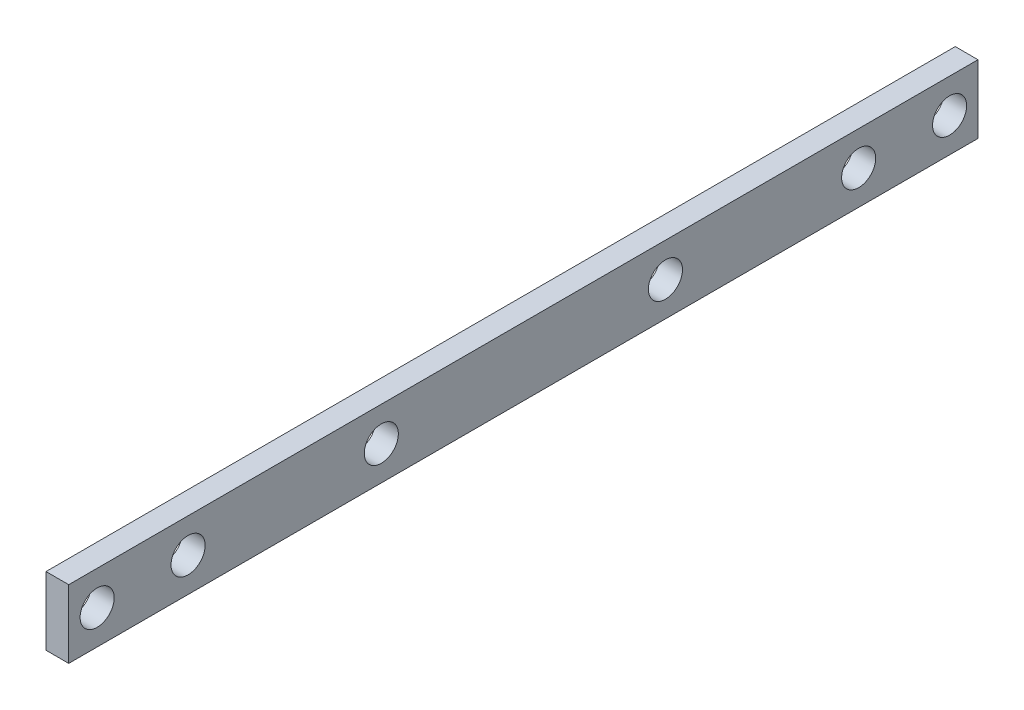
SolidWorks part; units mm, degrees
ref_plane "前视基准面" through (0, 0, 0) normal (0, 0, 1) x (1, 0, 0)
ref_plane "上视基准面" through (0, 0, 0) normal (0, 1, 0) x (1, 0, 0)
ref_plane "右视基准面" through (0, 0, 0) normal (1, 0, 0) x (0, 0, -1)
sketch "草图1" plane through (0, 0, 0) normal (1, 0, 0) x (0, 0, -1)
  line L0 (-40, 0) -> (40, 0) construction
  line L1 (-40, -3) -> (40, -3)
  line L2 (-40, -3) -> (-40, 3)
  line L3 (-40, 3) -> (40, 3)
  line L4 (40, -3) -> (40, 3)
  line L5 (-40, -3) -> (40, 3) construction
  line L6 (-40, 3) -> (40, -3) construction
  circle A0 centre (-37.5, 0) radius 1.5
  circle A1 centre (-12.5, 0) radius 1.5
  circle A2 centre (12.5, 0) radius 1.5
  circle A3 centre (37.5, 0) radius 1.5
  circle A4 centre (-29.5, 0) radius 1.5
  circle A5 centre (29.5, 0) radius 1.5
  point P0 (0, 0)
  dimension "D3" = 3
  dimension "D6" = 3
  dimension "D7" = 3
  dimension "D1" = 6
  dimension "D2" = 80
  dimension "D4" = 2.5
  dimension "D8" = 8
  dimension "D9" = 8
  dimension "D5" = 4
extrude "凸台-拉伸1" add sketch "草图1" along normal blind 2
